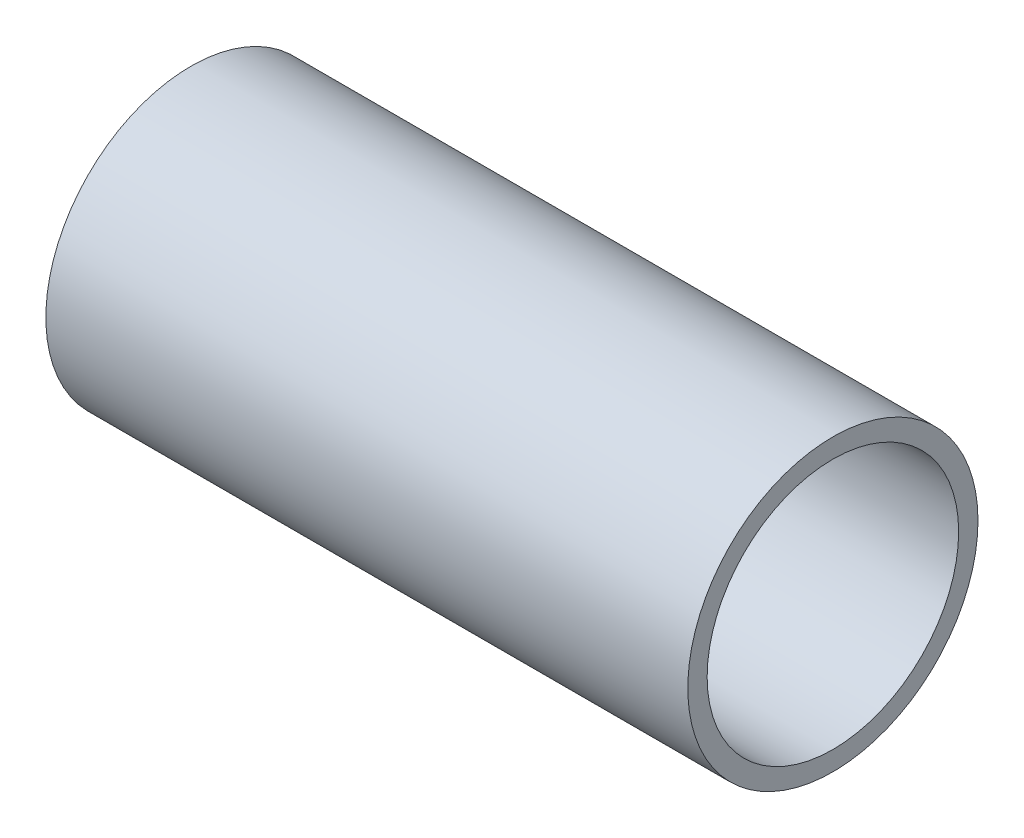
SolidWorks part; units mm, degrees
ref_plane "Plan de face" through (0, 0, 0) normal (0, 0, 1) x (1, 0, 0)
ref_plane "Plan de dessus" through (0, 0, 0) normal (0, 1, 0) x (1, 0, 0)
ref_plane "Plan de droite" through (0, 0, 0) normal (1, 0, 0) x (0, 0, -1)
sketch "Esquisse1" plane through (0, 0, 0) normal (1, 0, 0) x (0, 0, -1)
  circle A0 centre (0, 0) radius 16.5
  circle A1 centre (0, 0) radius 14.3
  dimension "D1" = 28.6
  dimension "D2" = 33
extrude "Boss.-Extru.1" add sketch "Esquisse1" along normal mid plane 73
